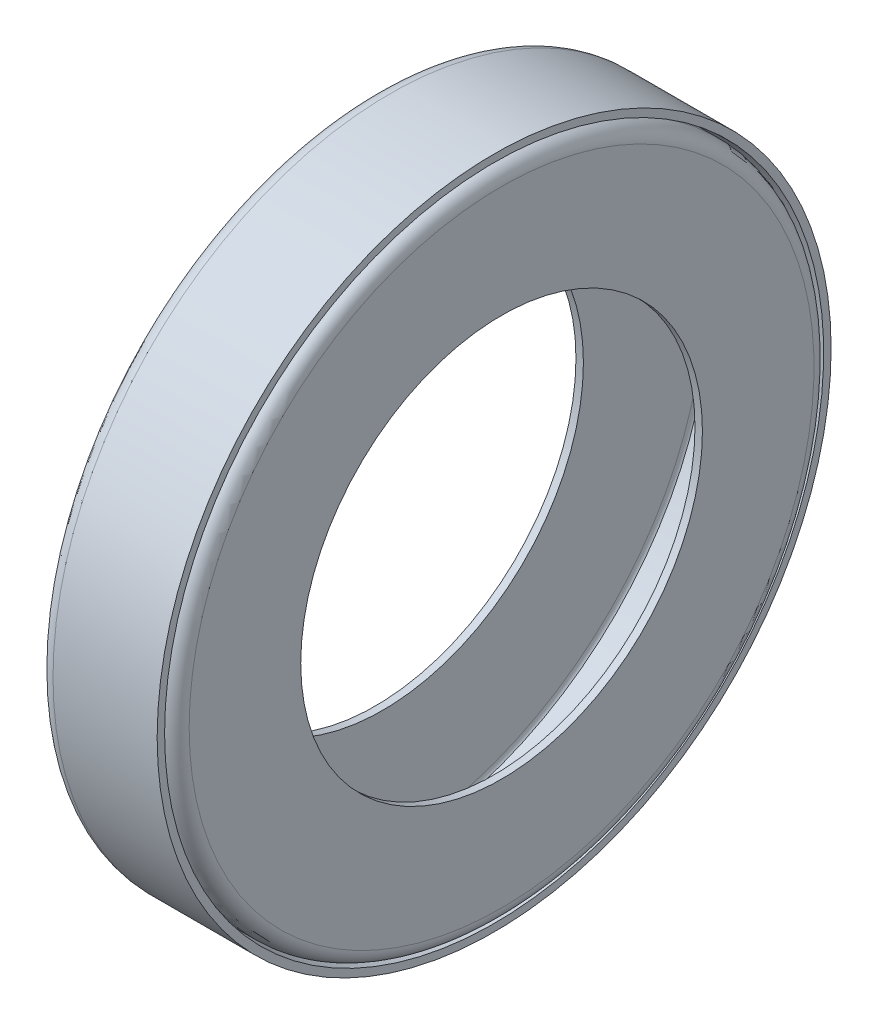
SolidWorks part; units mm, degrees
ref_plane "Front Plane" through (0, 0, 0) normal (0, 0, 1) x (1, 0, 0)
ref_plane "Top Plane" through (0, 0, 0) normal (0, 1, 0) x (1, 0, 0)
ref_plane "Right Plane" through (0, 0, 0) normal (1, 0, 0) x (0, 0, -1)
sketch "Sketch1" plane through (0, 0, 0) normal (0, 0, 1) x (1, 0, 0)
  line L0 (0, 27) -> (0, 45.3)
  line L1 (0, 45.3) -> (16, 45.3)
  line L2 (16, 45.3) -> (16, 44.3)
  line L3 (16, 44.3) -> (1, 44.3)
  line L4 (1, 44.3) -> (1, 27)
  line L5 (1, 27) -> (0, 27)
  line L6 (17, 27) -> (17, 44)
  line L7 (17, 44) -> (2, 44)
  line L8 (2, 44) -> (2, 43)
  line L9 (2, 43) -> (16, 43)
  line L10 (16, 43) -> (16, 27)
  line L11 (16, 27) -> (17, 27)
  line L12 (-12.2552, 0) -> (64.0467, 0) construction
  dimension "D1" = 1
  dimension "D2" = 1
  dimension "D3" = 15
  dimension "D4" = 14
  dimension "D5" = 1
  dimension "D6" = 1
  dimension "D7" = 15
  dimension "D8" = 0.3
  dimension "D9" = 27
  dimension "D10" = 43
revolve "Revolve1" add sketch "Sketch1" angle 360 about L12
fillet "Fillet1" radius 1 1 edges at (16, 0, 43)
fillet "Fillet2" radius 1 1 edges at (1, 0, 44.3)
fillet "Fillet3" radius 2 1 edges at (0, 0, 45.3)
fillet "Fillet4" radius 2 1 edges at (17, 0, 44)
